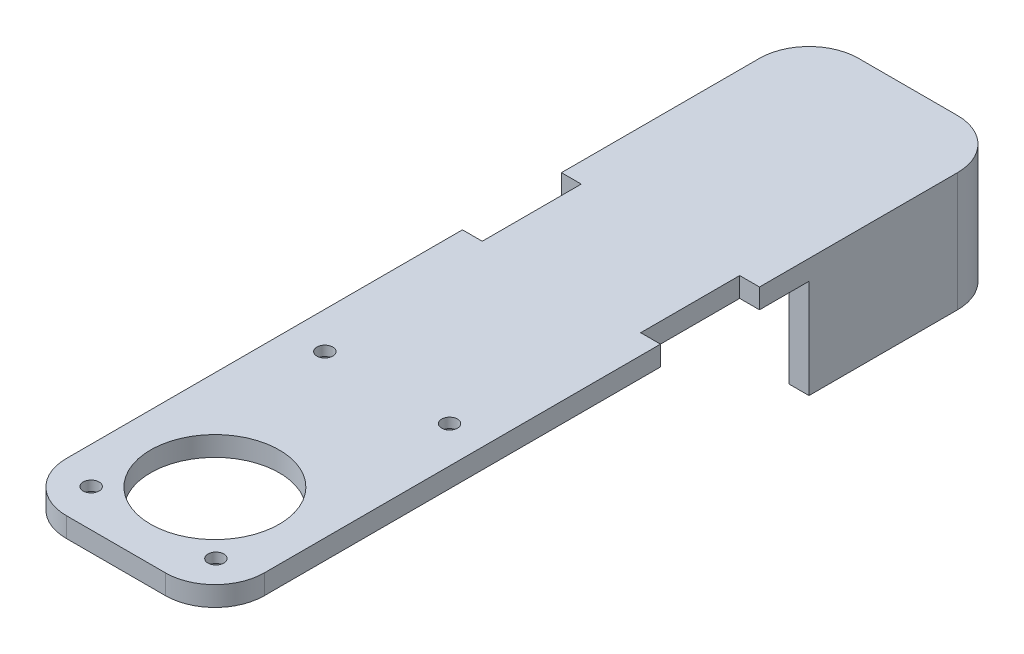
SolidWorks part; units mm, degrees
ref_plane "Front Plane" through (0, 0, 0) normal (0, 0, 1) x (1, 0, 0)
ref_plane "Top Plane" through (0, 0, 0) normal (0, 1, 0) x (1, 0, 0)
ref_plane "Right Plane" through (0, 0, 0) normal (1, 0, 0) x (0, 0, -1)
sketch "Sketch1" plane through (0, 0, 0) normal (0, 1, 0) x (1, 0, 0)
  line L1 (-12.7, -12.7) -> (12.7, -12.7)
  line L2 (-12.7, -12.7) -> (-12.7, 88.9)
  line L3 (-12.7, 88.9) -> (12.7, 88.9)
  line L4 (12.7, -12.7) -> (12.7, 88.9)
  circle A0 centre (0, 0) radius 8.255
  dimension "D1" = 16.51
  dimension "D2" = 12.7
  dimension "D3" = 25.4
  dimension "D4" = 12.7
  dimension "D5" = 101.6
extrude "Boss-Extrude1" add sketch "Sketch1" along normal blind 2.54
sketch "Sketch2" plane through (0, 2.54, 0) normal (0, 1, 0) x (1, 0, 0)
  line L0 (0, -55) -> (0, 55) construction
  circle A0 centre (-8, 22.098) radius 1.016
  circle A1 centre (8, 22.098) radius 1.016
  circle A2 centre (-8, -7.874) radius 1.016
  circle A3 centre (8, -7.874) radius 1.016
  point P0 (8, -7.874)
  point P1 (-8, -7.874)
  point P3 (8, 22.098)
  point P4 (-8, 22.098)
  dimension "D9" = 2.032
  dimension "D10" = 2.032
  dimension "D1" = 7.874
  dimension "D2" = 8
  dimension "D3" = 7.874
  dimension "D4" = 8
  dimension "D5" = 22.098
  dimension "D6" = 8
  dimension "D7" = 22.098
  dimension "D8" = 8
sketch "Sketch3" plane through (0, 0, 0) normal (0, -1, 0) x (1, 0, 0)
  line L1 (-12.7, -88.9) -> (-10.16, -88.9)
  line L2 (-12.7, -88.9) -> (-12.7, -63.5)
  line L3 (-12.7, -63.5) -> (-10.16, -63.5)
  line L4 (-10.16, -88.9) -> (-10.16, -63.5)
  line L5 (12.7, -88.9) -> (10.16, -88.9)
  line L6 (12.7, -88.9) -> (12.7, -63.5)
  line L7 (12.7, -63.5) -> (10.16, -63.5)
  line L8 (10.16, -88.9) -> (10.16, -63.5)
  line L10 (12.7, -88.9) -> (-12.7, -88.9) construction
  line L11 (12.7, 12.7) -> (12.7, -88.9) construction
  line L12 (-12.7, -88.9) -> (-12.7, 12.7) construction
  dimension "D1" = 2.54
  dimension "D2" = 25.4
  dimension "D3" = 2.54
  dimension "D4" = 25.4
  dimension "D5" = 0
  dimension "D6" = 0
extrude "Boss-Extrude2" add sketch "Sketch3" along normal blind 12.7
extrude "Cut-Extrude3" cut sketch "Sketch2" against normal blind 12.7
fillet "Fillet1" radius 6.35 4 edges at (12.7, 1.27, 12.7) (-12.7, 1.27, 12.7) (12.7, -5.08, -88.9) (-12.7, -5.08, -88.9)
sketch "Sketch5" plane through (0, 0, 0) normal (0, -1, 0) x (1, 0, 0)
  circle A0 centre (-8, -22.098) radius 2.032
  circle A1 centre (-8, 7.874) radius 2.032
  circle A2 centre (8, -22.098) radius 2.032
  circle A3 centre (8, 7.874) radius 2.032
  dimension "D1" = 4.064
  dimension "D2" = 4.064
  dimension "D3" = 4.064
  dimension "D4" = 4.064
extrude "Cut-Extrude4" cut sketch "Sketch5" against normal blind 1.27
sketch "Sketch6" plane through (0, 0, 0) normal (0, -1, 0) x (1, 0, 0)
  line L0 (12.7, -63.5) -> (10.16, -63.5) construction
  line L1 (10.16, -44.45) -> (12.7, -44.45)
  line L2 (10.16, -44.45) -> (10.16, -57.15)
  line L3 (10.16, -57.15) -> (12.7, -57.15)
  line L4 (12.7, -44.45) -> (12.7, -57.15)
  line L5 (12.7, 6.35) -> (12.7, -63.5) construction
  line L6 (-12.7, -63.5) -> (-12.7, 6.35) construction
  line L7 (-12.7, -44.45) -> (-10.16, -44.45)
  line L8 (-12.7, -44.45) -> (-12.7, -57.15)
  line L9 (-12.7, -57.15) -> (-10.16, -57.15)
  line L10 (-10.16, -44.45) -> (-10.16, -57.15)
  line L11 (-10.16, -63.5) -> (-12.7, -63.5) construction
  dimension "D1" = 12.7
  dimension "D2" = 2.54
  dimension "D3" = 6.35
  dimension "D4" = 0
  dimension "D5" = 12.7
  dimension "D6" = 2.54
  dimension "D7" = 0
  dimension "D8" = 6.35
extrude "Cut-Extrude5" cut sketch "Sketch6" against normal through all
